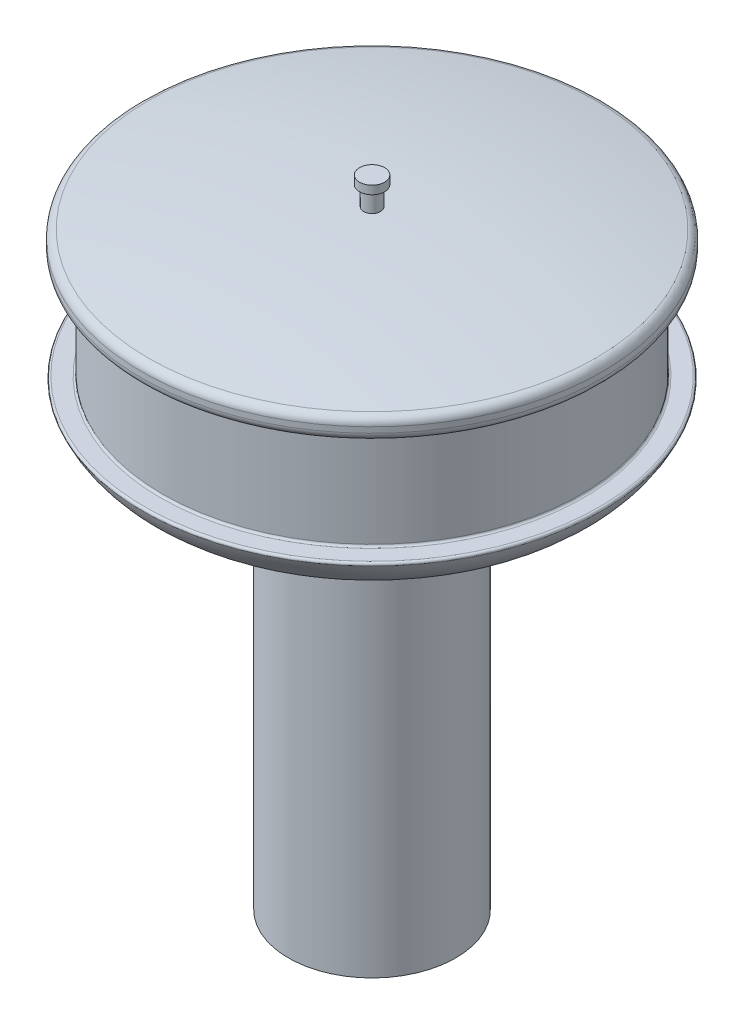
SolidWorks part; units mm, degrees
ref_plane "Front Plane" through (0, 0, 0) normal (0, 0, 1) x (1, 0, 0)
ref_plane "Top Plane" through (0, 0, 0) normal (0, 1, 0) x (1, 0, 0)
ref_plane "Right Plane" through (0, 0, 0) normal (1, 0, 0) x (0, 0, -1)
sketch "Sketch1" plane through (0, 0, 0) normal (0, 0, 1) x (1, 0, 0)
  line L0 (0, 0) -> (0, 132.9734) construction
  line L1 (20, -40) -> (20, 58)
  line L2 (22, 60) -> (40, 60)
  line L3 (54.263, 70.4322) -> (50.5, 70.4322)
  line L4 (50, 70.9322) -> (50, 94.9322)
  line L5 (50.5, 95.4322) -> (53, 95.4322)
  line L8 (0, 110) -> (2, 110)
  line L9 (2, 110) -> (2, 105.404)
  line L10 (55, 98.7703) -> (55, 97.4322)
  line L11 (0, 108) -> (0, 108)
  line L12 (0, 108) -> (0, 103.3969)
  line L13 (53, 98.7703) -> (53, 97.4322)
  line L14 (50.5, 97.4322) -> (53, 97.4322)
  line L15 (48, 70.9322) -> (48, 94.9322)
  line L16 (51.7783, 68.4322) -> (50.5, 68.4322)
  line L17 (22, 62) -> (40, 62)
  line L18 (18, -40) -> (18, 58)
  line L19 (0, 110) -> (0, 103.3969)
  line L20 (18, -40) -> (20, -40)
  arc A0 (40, 60) -> (54.7231, 69.7365) centre (40, 76) ccw
  arc A1 (2, 105.404) -> (53.3604, 100.7376) centre (2, -179.5794) cw
  arc A2 (22, 60) -> (20, 58) centre (22, 58) ccw
  arc A3 (53, 95.4322) -> (55, 97.4322) centre (53, 97.4322) ccw
  arc A4 (55, 98.7703) -> (53.3604, 100.7376) centre (53, 98.7703) ccw
  arc A5 (50.5, 95.4322) -> (50, 94.9322) centre (50.5, 94.9322) ccw
  arc A6 (50, 70.9322) -> (50.5, 70.4322) centre (50.5, 70.9322) ccw
  arc A7 (54.263, 70.4322) -> (54.7231, 69.7365) centre (54.263, 69.9322) cw
  arc A8 (0, 103.3969) -> (53, 98.7703) centre (2, -179.5794) cw
  arc A9 (53, 98.7703) -> (53, 98.7703) centre (53, 98.7703) ccw
  arc A10 (53, 97.4322) -> (53, 97.4322) centre (53, 97.4322) ccw
  arc A11 (50.5, 97.4322) -> (48, 94.9322) centre (50.5, 94.9322) ccw
  arc A12 (48, 70.9322) -> (50.5, 68.4322) centre (50.5, 70.9322) ccw
  arc A13 (51.7783, 68.4322) -> (51.7783, 68.4322) centre (51.7783, 68.4322) cw
  arc A14 (40, 62) -> (51.7783, 68.4322) centre (40, 76) ccw
  arc A15 (22, 62) -> (18, 58) centre (22, 58) ccw
  point P18 (20, 60)
  point P21 (55, 95.4322)
  point P24 (55, 100.4322)
  point P27 (50, 95.4322)
  point P30 (50, 70.4322)
  point P33 (55, 70.4322)
  dimension "D5" = 16
  dimension "D10" = 5
  dimension "D13" = 2
  dimension "D14" = 0.5
  dimension "D1" = 20
  dimension "D2" = 20
  dimension "D3" = 100
  dimension "D4" = 60
  dimension "D6" = 5
  dimension "D7" = 25
  dimension "D8" = 5
  dimension "D9" = 50
  dimension "D11" = 2
  dimension "D12" = 2
  dimension "D16" = 110
  dimension "D15" = 2
revolve "Revolve1" add sketch "Sketch1" angle 360 about L0
sketch "Sketch2" plane through (0, 110, 0) normal (0, 1, 0) x (1, 0, 0)
  circle A0 centre (0, 0) radius 3
  dimension "D1" = 6
extrude "Boss-Extrude1" add sketch "Sketch2" along normal blind 2
